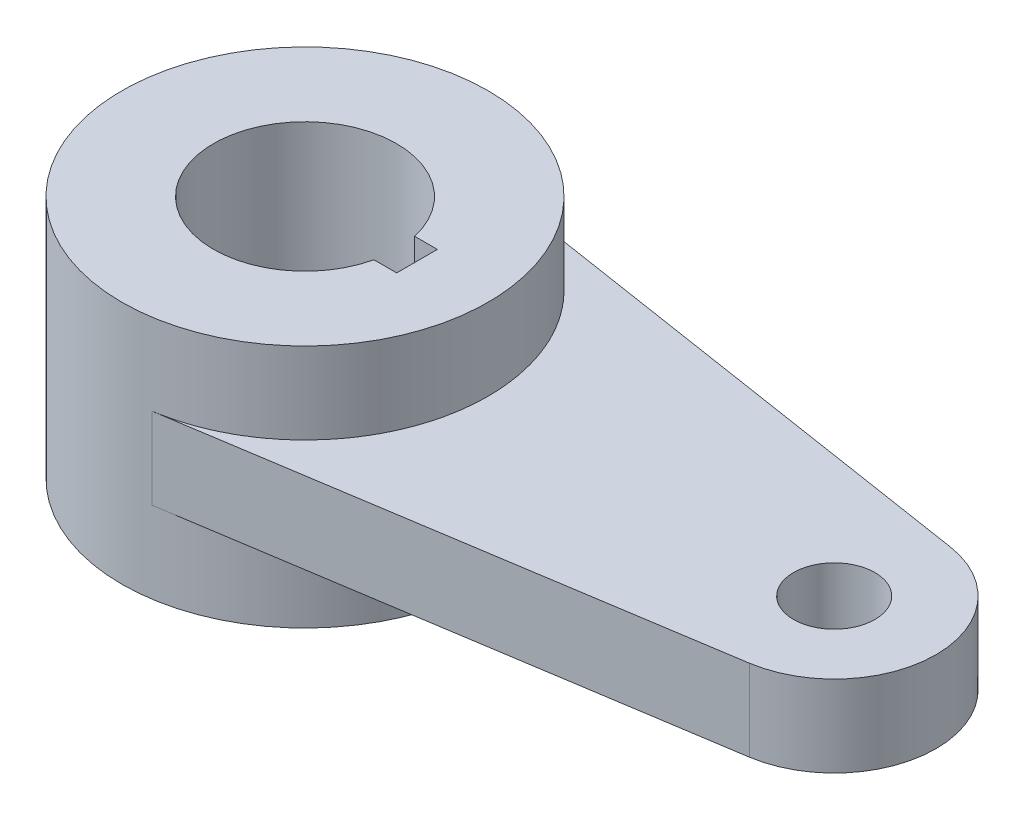
SolidWorks part; units mm, degrees
material "Cast Carbon Steel"
ref_plane "Front Plane" through (0, 0, 0) normal (0, 0, 1) x (1, 0, 0)
ref_plane "Top Plane" through (0, 0, 0) normal (0, 1, 0) x (1, 0, 0)
ref_plane "Right Plane" through (0, 0, 0) normal (1, 0, 0) x (0, 0, -1)
sketch "Sketch4" plane through (0, 0, 0) normal (0, 1, 0) x (1, 0, 0)
  circle A0 centre (0, 0) radius 28.575
  circle A1 centre (0, 0) radius 14.2875
  dimension "D1" = 57.15
  dimension "D2" = 28.575
extrude "Boss-Extrude1" add sketch "Sketch4" along normal mid plane 38.1
sketch "Sketch5" plane through (0, 0, 0) normal (0, 1, 0) x (1, 0, 0)
  line L0 (0, 0) -> (82.55, 0) construction
  line L1 (4.3962, 28.2348) -> (84.9923, 15.686)
  line L2 (4.3962, -28.2348) -> (84.9923, -15.686)
  circle A0 centre (0, 0) radius 28.575 construction
  arc A1 (4.3962, -28.2348) -> (4.3962, 28.2348) centre (0, 0) ccw
  arc A2 (84.9923, -15.686) -> (84.9923, 15.686) centre (82.55, 0) ccw
  circle A3 centre (82.55, 0) radius 6.35
  dimension "D1" = 31.75
  dimension "D2" = 12.7
  dimension "D3" = 82.55
extrude "Boss-Extrude2" add sketch "Sketch5" along normal mid plane 12.7 separate body
sketch "Sketch6" plane through (0, 19.05, 0) normal (0, 1, 0) x (1, 0, 0)
  line L1 (0, -3.175) -> (17.4752, -3.175)
  line L2 (0, -3.175) -> (0, 3.175)
  line L3 (0, 3.175) -> (17.4752, 3.175)
  line L4 (17.4752, -3.175) -> (17.4752, 3.175)
  line L5 (0, -3.175) -> (17.4752, 3.175) construction
  line L6 (0, 3.175) -> (17.4752, -3.175) construction
  point P0 (8.7376, 0)
  dimension "D1" = 17.4752
  dimension "D2" = 6.35
extrude "Cut-Extrude2" cut sketch "Sketch6" against normal up to surface (38.1 mm away) contours L1 L4 L3 L2 up to face at (0, -19.05, 28.575)
